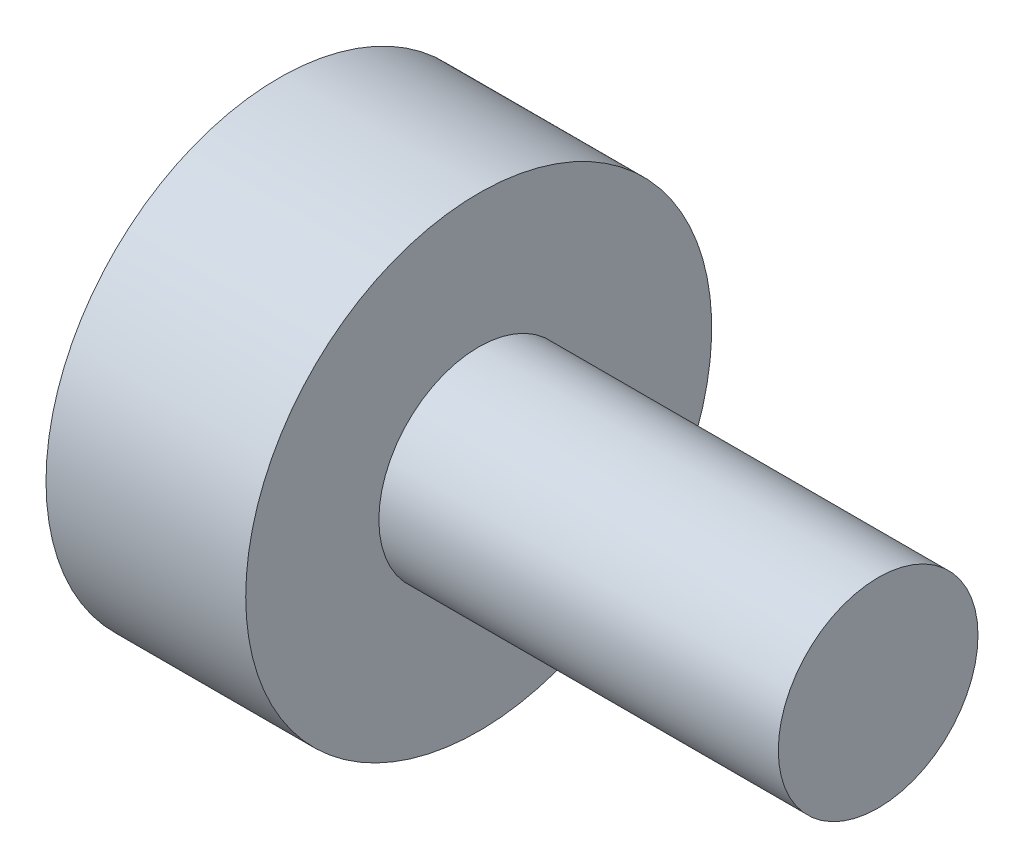
SolidWorks part; units mm, degrees
ref_plane "Спереди" through (0, 0, 0) normal (0, 0, 1) x (1, 0, 0)
ref_plane "Сверху" through (0, 0, 0) normal (0, 1, 0) x (1, 0, 0)
ref_plane "Справа" through (0, 0, 0) normal (1, 0, 0) x (0, 0, -1)
sketch "Эскиз1" plane through (0, 0, 0) normal (0, 0, 1) x (1, 0, 0)
  line L0 (0, 0) -> (100, 0)
  line L1 (0, 0) -> (0, 20)
  line L2 (0, 20) -> (10, 20)
  line L3 (10, 20) -> (10, 35)
  line L4 (10, 35) -> (40, 35)
  line L5 (40, 35) -> (40, 15)
  line L6 (40, 15) -> (100, 15)
  line L7 (100, 0) -> (100, 15)
revolve "Повернуть1" add sketch "Эскиз1" angle 360 about L0
sketch "Эскиз2" plane through (0, 0, 0) normal (1, 0, 0) x (0, 0, -1)
  circle A0 centre (0, 0) radius 5
extrude "Вырез-Вытянуть1" cut sketch "Эскиз2" along normal blind 20
sketch "Эскиз3" plane through (0, 0, 0) normal (1, 0, 0) x (0, 0, -1)
  circle A0 centre (0, 0) radius 9
extrude "Вырез-Вытянуть2" cut sketch "Эскиз3" along normal blind 5
